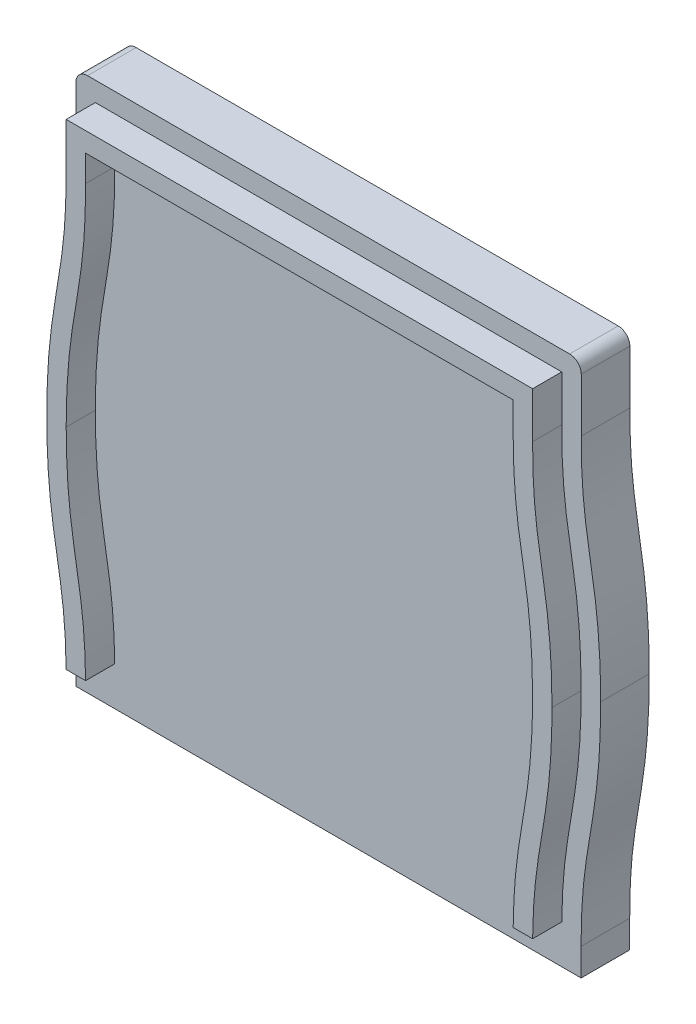
SolidWorks part; units mm, degrees
material "ABS"
ref_plane "Front Plane" through (0, 0, 0) normal (0, 0, 1) x (1, 0, 0)
ref_plane "Top Plane" through (0, 0, 0) normal (0, 1, 0) x (1, 0, 0)
ref_plane "Right Plane" through (0, 0, 0) normal (1, 0, 0) x (0, 0, -1)
sketch "Sketch1" plane through (0, 0, 0) normal (0, 0, 1) x (1, 0, 0)
  line L0 (28.0052, 53.0198) -> (28.0052, 0)
  line L1 (28.0052, 53.0198) -> (52.0052, 53.0198)
  line L3 (52, 0) -> (28.0052, 0)
  line L8 (52, 25.5198) -> (28.0052, 25.5198) construction
  line L9 (52, 2.9146) -> (52, 0)
  line L10 (52.0052, 53.0198) -> (52.0052, 48.303)
  spline S4 degree 3 poles (52.0052, 48.303) (52.005, 47.9998) (52.0077, 47.3796) (52.0248, 46.2504) (52.0673, 44.9541) (52.1497, 43.5635) (52.2984, 41.8577) (52.5521, 39.8914) (52.9651, 37.3899) (53.4502, 34.4928) (53.8024, 31.3838) (53.9424, 28.8625) (53.9933, 26.9404) (54.0003, 26.0584) (54, 25.6075) knots 0 0 0 0 0.03125 0.0625 0.125 0.1875 0.25 0.375 0.5 0.625 0.75 0.875 0.9375 1 1 1 1
  spline S5 degree 3 poles (54, 25.6075) (54, 25.1592) (53.9943, 24.2834) (53.9444, 22.3648) (53.8064, 19.8468) (53.4572, 16.7351) (52.9705, 13.8306) (52.554, 11.323) (52.2982, 9.3573) (52.1478, 7.6528) (52.0644, 6.2632) (52.0209, 4.9674) (52.003, 3.8383) (52, 3.2179) (52, 2.9146) knots 0 0 0 0 0.06277 0.125541 0.251082 0.376622 0.502163 0.627704 0.753245 0.816015 0.878786 0.941556 0.972941 1.004327 1.004327 1.004327 1.004327
  point P18 (52, 25.5198)
  dimension "D1" = 24
  dimension "D2" = 27.5
  dimension "D3" = 25.9948
  dimension "D4" = 2.9146
  dimension "D5" = 22.6929
extrude "Boss-Extrude1" add sketch "Sketch1" along normal blind 3
hole_wizard "M2 Clearance Hole1" [suppressed] positions "Sketch4" profile "Sketch5" hole size "M2" standard "ISO"
sketch "Sketch4" plane through (52, 0, 0) normal (1, 0, 0) x (0, 0, -1)
  line L0 (-10, 0) -> (0, 0) construction
  line L1 (-10, 0) -> (-10, 53) construction
  point P0 (-8, 1.5)
  dimension "D1" = 1.5
  dimension "D2" = 2
sketch "Sketch5" plane through (52, 1.5, 8) normal (0, 1, 0) x (0, 0, -1)
  line L0 (0, 0) -> (0, 50.72)
  line L1 (0, 50.72) -> (1.2, 49.999)
  line L2 (1.2, 49.999) -> (1.2, 0)
  line L5 (1.2, 0) -> (0, 0)
  line L10 (0, 50.72) -> (-1.2, 49.999) construction
  line L11 (0, -6.35) -> (0, 107.95) construction
  dimension "Hole Dia." = 2.4
  dimension "Hole Depth" = 49.999
  dimension "Drill Angle" = 118
ref_plane "Plane1" through (0, 0, 1.5) normal (0, 0, 1) x (1, 0, 0)
mirror "Mirror1" [suppressed] about plane through (0, 0, 1.5) normal (0, 0, 1)
ref_plane "Plane2" [suppressed] through (26, 0, 0) normal (-1, 0, 0) x (0, 0, 1)
mirror "Mirror2" [suppressed] about plane through (26, 0, 0) normal (-1, 0, 0)
fillet "Fillet2" [suppressed] radius 2
fillet "Fillet6" [suppressed] radius 2
mirror "Mirror3" about plane through (28.0052, 53.0198, 3) normal (1, 0, 0) of "Boss-Extrude1"
ref_plane "Plane3" through (4.0052, 48.303, 0) normal (0, 1, 0) x (1, 0, 0)
sketch "Sketch7" plane through (0, 0, 0) normal (0, 0, -1) x (-1, 0, 0)
  line L1 (-54, 0) -> (-2.0104, 0)
  line L10 (-54, 0) -> (-54, 2.8267)
  line L11 (-54.0129, 48.3021) -> (-54.0129, 55.0198)
  line L12 (-54.0129, 55.0198) -> (-2.0052, 55.0198)
  line L13 (-2.0052, 48.3907) -> (-2.0052, 55.0198)
  line L14 (-2.0104, 0) -> (-2.0104, 2.8267)
  spline S12 degree 3 poles (-54, 2.8267) (-54.0001, 3.1244) (-54.0033, 3.7345) (-54.0212, 4.8366) (-54.0641, 6.0961) (-54.1454, 7.4337) (-54.2909, 9.0686) (-54.5382, 10.9594) (-54.9514, 13.4387) (-55.4519, 16.426) (-55.8133, 19.6741) (-55.953, 22.2788) (-56.0029, 24.2484) (-56.0075, 25.1467) (-56.0077, 25.6066) knots 0 0 0 0 0.031513 0.063026 0.126053 0.189079 0.252105 0.378158 0.50421 0.630263 0.756315 0.882368 0.945394 1.00842 1.00842 1.00842 1.00842
  spline S13 degree 3 poles (-56.0077, 25.6066) (-56.0079, 26.0696) (-56.0007, 26.9758) (-55.9486, 28.9464) (-55.8044, 31.5491) (-55.438, 34.7796) (-54.9426, 37.7355) (-54.5374, 40.1925) (-54.2946, 42.0768) (-54.1523, 43.7084) (-54.0732, 45.0435) (-54.032, 46.2995) (-54.0153, 47.3981) (-54.0127, 48.0056) (-54.0129, 48.3021) knots 0.000026 0.000026 0.000026 0.000026 0.062526 0.125025 0.250024 0.375024 0.500023 0.625022 0.750021 0.812521 0.875021 0.93752 0.96877 1.00002 1.00002 1.00002 1.00002
  spline S14 degree 3 poles (-2.0052, 48.3907) (-2.0053, 48.0931) (-2.0024, 47.4831) (-1.9853, 46.3806) (-1.9433, 45.1203) (-1.8631, 43.7813) (-1.7192, 42.1448) (-1.4739, 40.2534) (-1.0644, 37.7814) (-0.5659, 34.8038) (-0.2013, 31.5596) (-0.0594, 28.949) (-0.0084, 26.9786) (-0.0026, 26.0709) (-0.0027, 25.6073) knots -0.004038 -0.004038 -0.004038 -0.004038 0.027339 0.058716 0.12147 0.184223 0.246977 0.372484 0.497991 0.623498 0.749005 0.874513 0.937266 1.00002 1.00002 1.00002 1.00002
  spline S15 degree 3 poles (-0.0027, 25.6073) (-0.0027, 25.146) (-0.0086, 24.2456) (-0.0599, 22.268) (-0.2025, 19.661) (-0.5673, 16.4138) (-1.0667, 13.4368) (-1.477, 10.9631) (-1.7228, 9.0722) (-1.8672, 7.4358) (-1.9477, 6.097) (-1.99, 4.8369) (-2.0074, 3.7343) (-2.0104, 3.1243) (-2.0104, 2.8267) knots 0 0 0 0 0.062769 0.125538 0.251075 0.376613 0.50215 0.627688 0.753225 0.815994 0.878763 0.941531 0.972916 1.0043 1.0043 1.0043 1.0043
  dimension "D1" = 52.0077
extrude "Boss-Extrude2" add sketch "Sketch7" along normal blind 5 separate body
fillet "Fillet7" radius 1.2 2 edges at (54.0129, 55.0198, -2.5) (2.0052, 55.0198, -2.5)
sketch "Sketch8" plane through (0, 0, 3) normal (0, 0, 1) x (1, 0, 0)
  line L0 (50.0052, 51.0198) -> (6.0052, 51.0198)
  line L1 (6.0052, 51.0198) -> (6.0052, 48.3036)
  line L2 (6.0104, 2.9146) -> (6.0104, 2)
  line L3 (6.0104, 2) -> (50, 2)
  line L4 (50, 2) -> (50, 2.9146)
  line L5 (50.0052, 48.3036) -> (50.0052, 51.0198)
  line L6 (52.0052, 53.0198) -> (4.0052, 53.0198)
  line L7 (4.0052, 53.0198) -> (4.0052, 48.303)
  line L8 (4.0104, 2.9146) -> (4.0104, 0)
  line L9 (4.0104, 0) -> (52, 0)
  line L10 (52, 0) -> (52, 2.9146)
  line L11 (52.0052, 48.303) -> (52.0052, 53.0198)
  line L12 (52.0052, 53.0198) -> (4.0052, 53.0198)
  line L13 (4.0052, 53.0198) -> (4.0052, 48.303)
  line L14 (4.0104, 2.9146) -> (4.0104, 0)
  line L15 (4.0104, 0) -> (52, 0)
  line L16 (52, 0) -> (52, 2.9146)
  line L17 (52.0052, 48.303) -> (52.0052, 53.0198)
  spline S0 degree 1 poles (6.0052, 48.3036) (4.0104, 25.6081) knots 0 0 1 1 construction
  spline S1 degree 1 poles (4.0104, 25.6081) (6.0104, 2.9146) knots 0 0 1 1 construction
  spline S2 degree 1 poles (50, 2.9146) (52, 25.6081) knots 0 0 1 1 construction
  spline S3 degree 1 poles (52, 25.6081) (50.0052, 48.3036) knots 0 0 1 1 construction
  spline S4 degree 3 poles (-19.0248, -3951.3324) (-0.7104, 129.8363) (4.2488, 63.6328) (3.9856, 46.2504) (3.9431, 44.9541) (3.8607, 43.5635) (3.712, 41.8577) (3.4583, 39.8914) (3.0453, 37.3899) (2.5602, 34.4928) (2.208, 31.3838) (2.068, 28.8625) (1.3731, 2.6116) (13.4795, 32.1191) (-80.3928, -3973.3147) knots -1.799286 -1.799286 -1.799286 -1.799286 0.03125 0.0625 0.125 0.1875 0.25 0.375 0.5 0.625 0.75 0.875 0.9375 4.164231 4.164231 4.164231 4.164231 only from (4.0052, 48.303) to (2.0104, 25.6075)
  spline S5 degree 3 poles (-216.2237, 4019.4307) (13.601, 17.1228) (1.3965, 48.1307) (2.066, 22.3648) (2.204, 19.8468) (2.5532, 16.7351) (3.0399, 13.8306) (3.4564, 11.323) (3.7122, 9.3573) (3.8626, 7.6528) (3.9461, 6.2632) (3.9895, 4.9674) (4.2636, -12.39) (-0.6654, -78.6485) (-21.4049, 4002.6903) knots -3.120921 -3.120921 -3.120921 -3.120921 0.06277 0.125541 0.251082 0.376622 0.502163 0.627704 0.753245 0.816015 0.878786 0.941556 0.972941 2.808759 2.808759 2.808759 2.808759 only from (2.0104, 25.6075) to (4.0104, 2.9146)
  spline S6 degree 3 poles (77.4151, 4002.6498) (56.6758, -78.6481) (51.7468, -12.39) (52.0209, 4.9674) (52.0644, 6.2632) (52.1478, 7.6528) (52.2982, 9.3573) (52.554, 11.323) (52.9705, 13.8306) (53.4572, 16.7351) (53.8064, 19.8468) (53.9444, 22.3648) (54.6139, 48.1307) (42.4094, 17.1229) (272.2336, 4019.4213) knots -1.804426 -1.804426 -1.804426 -1.804426 0.031385 0.06277 0.125541 0.188311 0.251082 0.376622 0.502163 0.627704 0.753245 0.878786 0.941556 4.125245 4.125245 4.125245 4.125245 only from (52, 2.9146) to (54, 25.6075)
  spline S7 degree 3 poles (136.4046, -3973.3715) (42.5308, 32.1194) (54.6373, 2.6115) (53.9424, 28.8625) (53.8024, 31.3838) (53.4502, 34.4928) (52.9651, 37.3899) (52.5521, 39.8914) (52.2984, 41.8577) (52.1497, 43.5635) (52.0673, 44.9541) (52.0248, 46.2504) (51.7616, 63.6328) (56.7208, 129.8362) (75.0352, -3951.3314) knots -3.164247 -3.164247 -3.164247 -3.164247 0.0625 0.125 0.25 0.375 0.5 0.625 0.75 0.8125 0.875 0.9375 0.96875 2.799285 2.799285 2.799285 2.799285 only from (54, 25.6075) to (52.0052, 48.303)
  spline S8 degree 3 poles (4.0052, 48.303) (4.0054, 47.9998) (4.0027, 47.3796) (3.9856, 46.2504) (3.9431, 44.9541) (3.8607, 43.5635) (3.712, 41.8577) (3.4583, 39.8914) (3.0453, 37.3899) (2.5602, 34.4928) (2.208, 31.3838) (2.068, 28.8625) (2.0171, 26.9404) (2.0102, 26.0584) (2.0104, 25.6075) knots 0 0 0 0 0.03125 0.0625 0.125 0.1875 0.25 0.375 0.5 0.625 0.75 0.875 0.9375 1 1 1 1
  spline S9 degree 3 poles (2.0104, 25.6075) (2.0104, 25.1592) (2.0161, 24.2834) (2.066, 22.3648) (2.204, 19.8468) (2.5532, 16.7351) (3.0399, 13.8306) (3.4564, 11.323) (3.7122, 9.3573) (3.8626, 7.6528) (3.9461, 6.2632) (3.9895, 4.9674) (4.0074, 3.8383) (4.0104, 3.2179) (4.0104, 2.9146) knots 0 0 0 0 0.06277 0.125541 0.251082 0.376622 0.502163 0.627704 0.753245 0.816015 0.878786 0.941556 0.972941 1.004327 1.004327 1.004327 1.004327
  spline S10 degree 3 poles (52, 2.9146) (52, 3.2179) (52.003, 3.8383) (52.0209, 4.9674) (52.0644, 6.2632) (52.1478, 7.6528) (52.2982, 9.3573) (52.554, 11.323) (52.9705, 13.8306) (53.4572, 16.7351) (53.8064, 19.8468) (53.9444, 22.3648) (53.9943, 24.2834) (54, 25.1592) (54, 25.6075) knots 0 0 0 0 0.031385 0.06277 0.125541 0.188311 0.251082 0.376622 0.502163 0.627704 0.753245 0.878786 0.941556 1.004327 1.004327 1.004327 1.004327
  spline S11 degree 3 poles (54, 25.6075) (54.0003, 26.0584) (53.9933, 26.9404) (53.9424, 28.8625) (53.8024, 31.3838) (53.4502, 34.4928) (52.9651, 37.3899) (52.5521, 39.8914) (52.2984, 41.8577) (52.1497, 43.5635) (52.0673, 44.9541) (52.0248, 46.2504) (52.0077, 47.3796) (52.005, 47.9998) (52.0052, 48.303) knots 0 0 0 0 0.0625 0.125 0.25 0.375 0.5 0.625 0.75 0.8125 0.875 0.9375 0.96875 1 1 1 1
  spline S12 degree 3 poles (6.0052, 48.3036) (6.0054, 47.9937) (6.0027, 47.3607) (5.9851, 46.201) (5.9413, 44.8644) (5.8557, 43.4182) (5.7005, 41.6382) (5.436, 39.59) (5.0151, 37.044) (4.5404, 34.2056) (4.2024, 31.2182) (4.0665, 28.7783) (4.0169, 26.9046) (4.0102, 26.0469) (4.0104, 25.6081) knots 0.00002 0.00002 0.00002 0.00002 0.03127 0.06252 0.12502 0.187521 0.250021 0.375022 0.500023 0.625024 0.750025 0.875026 0.937526 1.000027 1.000027 1.000027 1.000027
  spline S13 degree 3 poles (4.0104, 25.6081) (4.0104, 25.1709) (4.016, 24.3161) (4.0645, 22.449) (4.1985, 20.0098) (4.5335, 17.021) (5.0095, 14.1775) (5.4337, 11.6264) (5.7005, 9.5787) (5.8574, 7.7996) (5.9442, 6.3541) (5.989, 5.0177) (6.0073, 3.8579) (6.0104, 3.2246) (6.0104, 2.9146) knots -0.000027 -0.000027 -0.000027 -0.000027 0.062745 0.125517 0.251061 0.376606 0.50215 0.627694 0.753238 0.81601 0.878782 0.941555 0.972941 1.004327 1.004327 1.004327 1.004327
  spline S14 degree 3 poles (50, 2.9146) (50, 3.2246) (50.0031, 3.8579) (50.0214, 5.0177) (50.0662, 6.3541) (50.153, 7.7996) (50.3099, 9.5787) (50.5767, 11.6264) (51.0009, 14.1775) (51.4769, 17.021) (51.8119, 20.0098) (51.9459, 22.449) (51.9945, 24.3161) (52, 25.1709) (52, 25.6081) knots 0 0 0 0 0.031386 0.062772 0.125544 0.188316 0.251088 0.376633 0.502177 0.627721 0.753265 0.878809 0.941581 1.004354 1.004354 1.004354 1.004354
  spline S15 degree 3 poles (52, 25.6081) (52.0003, 26.0469) (51.9935, 26.9046) (51.9439, 28.7783) (51.808, 31.2182) (51.47, 34.2056) (50.9954, 37.044) (50.5745, 39.59) (50.3099, 41.6382) (50.1547, 43.4182) (50.0691, 44.8644) (50.0253, 46.201) (50.0078, 47.3607) (50.005, 47.9937) (50.0052, 48.3036) knots -0.000027 -0.000027 -0.000027 -0.000027 0.062474 0.124974 0.249975 0.374976 0.499977 0.624978 0.749979 0.812479 0.87498 0.93748 0.96873 0.99998 0.99998 0.99998 0.99998
  dimension "D1" = 0
  dimension "D2" = 2
extrude "Cut-Extrude1" cut sketch "Sketch8" against normal up to surface (3 mm away) contours S14 S15 L5 L0 L1 S12 S13 L2 L3 L4 up to face at (28.0079, 30.9743, 0)
sketch "Sketch9" plane through (0, 0, 3) normal (0, 0, 1) x (1, 0, 0)
  line L0 (54, 0) -> (2.0104, 0) construction
  line L1 (3.0104, 0) -> (53, 0)
  line L2 (3.0104, 0) -> (3.0104, 4)
  line L3 (3.0104, 4) -> (53, 4)
  line L4 (53, 0) -> (53, 4)
  dimension "D1" = 1
  dimension "D2" = 1
  dimension "D3" = 4
extrude "Cut-Extrude2" cut sketch "Sketch9" against normal up to surface (3 mm away) up to face at (28.0079, 30.9743, 0)
